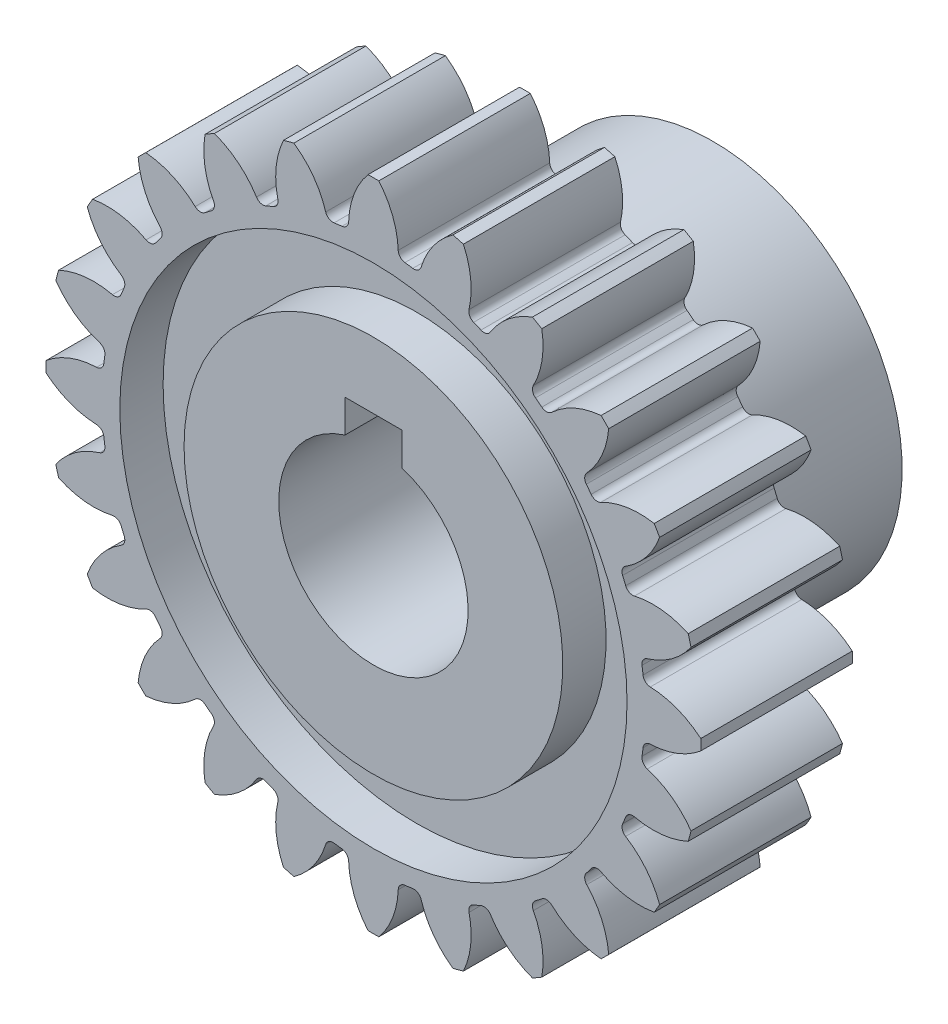
SolidWorks part; units mm, degrees
ref_plane "Front Plane" through (0, 0, 0) normal (0, 0, 1) x (1, 0, 0)
ref_plane "Top Plane" through (0, 0, 0) normal (0, 1, 0) x (1, 0, 0)
ref_plane "Right Plane" through (0, 0, 0) normal (1, 0, 0) x (0, 0, -1)
sketch "Sketch1" plane through (0, 0, 0) normal (1, 0, 0) x (0, 0, -1)
  line L0 (-7.112, 0) -> (-7.112, 13.7223)
  line L1 (-7.112, 13.7223) -> (-0.762, 13.7223)
  line L2 (-0.762, 13.7223) -> (-0.762, 7.9375)
  line L3 (-0.762, 7.9375) -> (7.112, 7.9375)
  line L4 (7.112, 7.9375) -> (7.112, 0)
  line L5 (7.112, 0) -> (-7.112, 0) construction
  line L6 (-7.112, 3.175) -> (7.112, 3.175)
  point P9 (-7.112, 10.6299)
  dimension "OD" = 27.4447
  dimension "Face Width" = 6.35
  dimension "Hub Width" = 7.874
  dimension "Hub Diameter" = 15.875
  dimension "For Shaft Diameter" = 6.35
  dimension "Overall Width" = 14.224
  dimension "Under Cut Diameter" = 21.2598
sketch "Sketch2" plane through (0, 0, 0) normal (0, 0, 1) x (1, 0, 0)
  line L0 (-1.3313, 11.2989) -> (-0.4492, 13.7223)
  line L1 (-0.4492, 13.7223) -> (0.4492, 13.7223)
  line L2 (0.4492, 13.7223) -> (1.3313, 11.2989)
  line L3 (0, 13.7223) -> (0, 0) construction
  line L4 (0, 0) -> (-1.7911, 13.605) construction
  line L5 (0, 0) -> (1.7911, 13.605) construction
  line L6 (-4.2103, 10.5694) -> (-3.9855, 13.1385)
  line L7 (-3.9855, 13.1385) -> (-3.1177, 13.371)
  line L8 (-3.1177, 13.371) -> (-1.6385, 11.2585)
  line L9 (-3.5516, 13.2548) -> (0, 0) construction
  line L11 (-0.4492, 13.7223) -> (0, 13.7223) construction
  line L12 (-0.8312, 12.6728) -> (0.8312, 12.6728) construction
  circle A0 centre (0, 0) radius 12.7 construction
  circle A2 centre (0, 0) radius 13.7223
  circle A3 centre (0, 0) radius 11.3771
  arc A5 (-0.2246, 13.7223) -> (-1.0378, 11.3296) centre (2.4404, 11.482) ccw
  arc A6 (1.0378, 11.3296) -> (0.2246, 13.7223) centre (-2.4404, 11.482) ccw
  arc A7 (-1.9298, 11.2122) -> (-3.3347, 13.3129) centre (-5.329, 10.4591) ccw
  arc A8 (-0.8312, 12.6728) -> (0.8312, 12.6728) centre (0, 0) cw
  point P3 (0, 12.7)
  point P5 (3.287, 12.2673)
  point P6 (-10.9985, 6.35)
  point P9 (6.35, 10.9985)
  point P10 (8.9803, 8.9803)
  point P11 (10.9985, 6.35)
  point P12 (12.2673, 3.287)
  point P13 (12.7, 0)
  point P14 (12.2673, -3.287)
  point P15 (10.9985, -6.35)
  point P16 (8.9803, -8.9803)
  point P17 (6.35, -10.9985)
  point P18 (3.287, -12.2673)
  point P19 (0, -12.7)
  point P20 (-3.287, -12.2673)
  point P21 (-6.35, -10.9985)
  point P22 (-8.9803, -8.9803)
  point P23 (-10.9985, -6.35)
  point P24 (-12.2673, -3.287)
  point P25 (-12.7, 0)
  point P26 (-12.2673, 3.287)
  point P27 (-8.9803, 8.9803)
  point P28 (-6.35, 10.9985)
  point P29 (-3.287, 12.2673)
  point P31 (0, 0)
  dimension "Gear Pitch Diameter" = 25.4
  dimension "Pressure Angle" = 20
  dimension "Addendum" = 1.0223
  dimension "Dedendum" = 1.3229
  dimension "D1" = 15
  dimension "D2" = 1.6624
  dimension "Number of Teeth" = 24
sketch "Sketch3" plane through (0, 0, 0) normal (1, 0, 0) x (0, 0, -1)
  line L0 (-7.112, 13.7223) -> (-0.762, 13.7223) construction
  line L1 (7.112, 7.9375) -> (7.112, 0) construction
  line L2 (-0.762, 7.9375) -> (7.112, 7.9375) construction
  line L3 (-0.762, 13.7223) -> (-0.762, 7.9375) construction
  line L4 (-7.112, 0) -> (-7.112, 13.7223) construction
  line L5 (-7.112, 3.175) -> (7.112, 3.175) construction
  line L6 (-7.112, 13.7223) -> (-0.762, 13.7223)
  line L7 (7.112, 7.9375) -> (7.112, 3.175)
  line L8 (-7.112, 7.9375) -> (-5.2977, 7.9375)
  line L9 (-0.762, 13.7223) -> (-0.762, 10.6299)
  line L10 (-7.112, 3.175) -> (-7.112, 7.9375)
  line L11 (-7.112, 3.175) -> (7.112, 3.175)
  line L12 (-7.112, 10.6299) -> (-5.2977, 10.6299)
  line L13 (-5.2977, 10.6299) -> (-5.2977, 7.9375)
  line L14 (-0.762, 10.6299) -> (-2.5763, 10.6299)
  line L15 (-2.5763, 10.6299) -> (-2.5763, 7.9375)
  line L16 (-2.5763, 7.9375) -> (7.112, 7.9375)
  line L17 (-7.112, 10.6299) -> (-7.112, 13.7223)
  dimension "D1" = 1.8143
revolve "Revolve1" add sketch "Sketch3" angle 360 about L5
sketch "Sketch4" plane through (0, 0, 7.112) normal (0, 0, 1) x (1, 0, 0)
  arc A1 (-0.2246, 13.7223) -> (-1.0378, 11.3296) centre (2.4404, 11.482) ccw construction
  arc A2 (-1.9298, 11.2122) -> (-3.3347, 13.3129) centre (-5.329, 10.4591) ccw construction
  arc A3 (-0.2262, 13.7205) -> (-1.039, 11.6045) centre (2.4404, 11.482) ccw
  arc A4 (-1.9998, 11.478) -> (-3.3327, 13.3115) centre (-5.329, 10.4591) ccw
  circle A5 centre (0, 0) radius 13.7223 construction
  arc A6 (-0.2262, 13.7205) -> (-3.3327, 13.3115) centre (0, 0) ccw
  circle A7 centre (0, 0) radius 11.3771 construction
  arc A8 (-1.3195, 11.3003) -> (-1.6502, 11.2568) centre (0, 0) ccw
  arc A9 (-1.9998, 11.478) -> (-1.6502, 11.2568) centre (-1.6962, 11.5709) ccw
  arc A10 (-1.3195, 11.3003) -> (-1.039, 11.6045) centre (-1.3563, 11.6157) ccw
  dimension "D1" = 0.3175
extrude "Cut-Extrude1" cut sketch "Sketch4" against normal through all both and the other way through all
pattern_circular "CirPattern1" count 24 over 360 about axis through (0, 0, 0) along (0, 0, 1) of "Cut-Extrude1"
sketch "Sketch5" plane through (0, 0, -7.112) normal (0, 0, -1) x (-1, 0, 0)
  line L1 (-1.1906, 5.1594) -> (1.1906, 5.1594)
  line L2 (-1.1906, 5.1594) -> (-1.1906, 2.7781)
  line L3 (-1.1906, 2.7781) -> (1.1906, 2.7781)
  line L4 (1.1906, 5.1594) -> (1.1906, 2.7781)
  line L5 (-1.1906, 5.1594) -> (1.1906, 2.7781) construction
  line L6 (-1.1906, 2.7781) -> (1.1906, 5.1594) construction
  circle A0 centre (0, 0) radius 3.9688
  point P3 (0, 3.9687)
  circle M4 centre (0, 0) radius 3.175
  dimension "D1" = 7.9375
  dimension "D2" = 2.3813
extrude "Cut-Extrude2" cut sketch "Sketch5" against normal through all contours L2 A0 L4 M4 | L4 A0 L2 M4 | A0 L4 L1 L2
equation "\"Dedendum@Sketch2\" = 1.25 /  ( \"Number of Teeth@Sketch2\" / \"Gear Pitch Diameter@Sketch2\" ) "
equation "\"D1@Sketch2\"=360/\"Number of Teeth@Sketch2\""
equation "\"D1@Sketch4\"=.3/(\"Number of Teeth@Sketch2\"/\"Gear Pitch Diameter@Sketch2\")"
equation "\"D1@CirPattern1\"=\"Number of Teeth@Sketch2\""
equation "\"D2@Sketch2\"=1.5708/(\"Number of Teeth@Sketch2\"/\"Gear Pitch Diameter@Sketch2\")"
equation "\"D1@Sketch3\"=\"Face Width@Sketch1\"/3.5"
